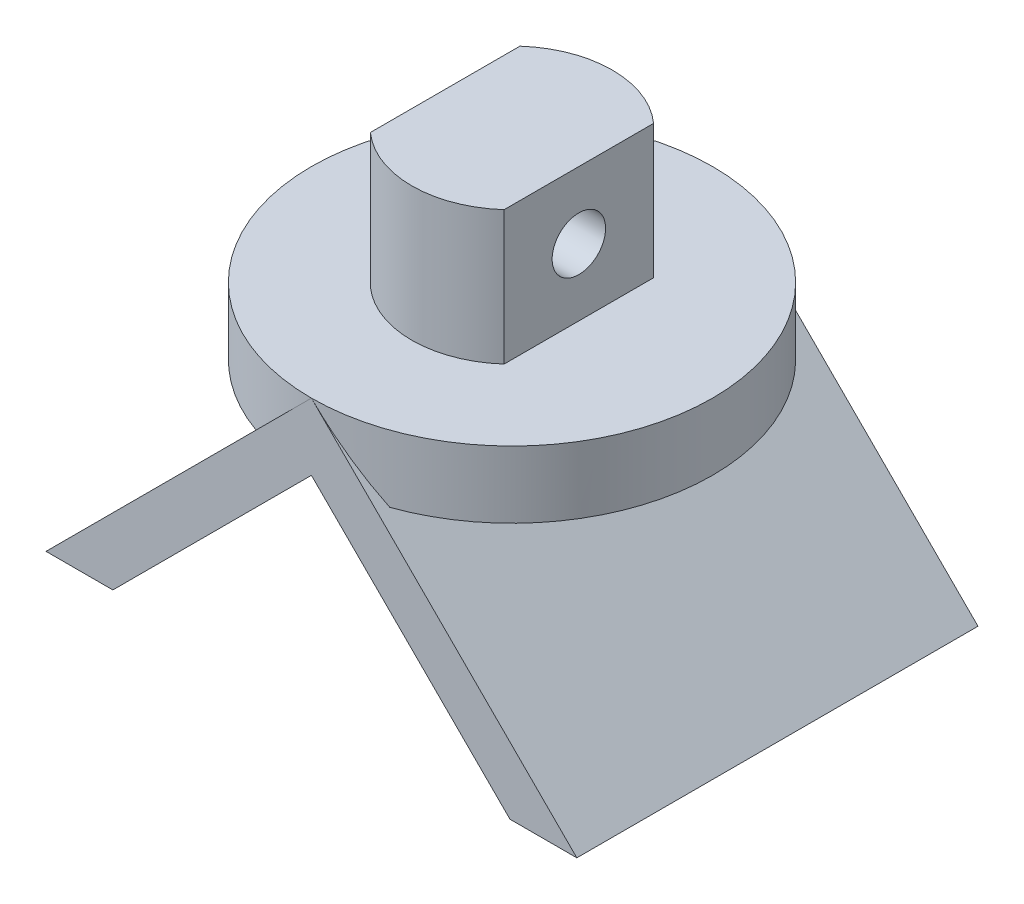
SolidWorks part; units mm, degrees
ref_plane "Plan de face" through (0, 0, 0) normal (0, 0, 1) x (1, 0, 0)
ref_plane "Plan de dessus" through (0, 0, 0) normal (0, 1, 0) x (1, 0, 0)
ref_plane "Plan de droite" through (0, 0, 0) normal (1, 0, 0) x (0, 0, -1)
sketch "Esquisse1" plane through (0, 0, 0) normal (0, 0, 1) x (1, 0, 0)
  line L0 (-14.8492, 0) -> (0, 14.8492)
  line L1 (0, 14.8492) -> (14.8492, 0)
  line L2 (14.8492, 0) -> (19.8492, 0)
  line L3 (19.8492, 0) -> (0, 19.8492)
  line L4 (0, 19.8492) -> (-19.8492, 0)
  line L5 (-19.8492, 0) -> (-14.8492, 0)
  line L6 (-14.8492, 0) -> (14.8492, 0) construction
  point P5 (0, 0)
  dimension "D1" = 5
  dimension "D2" = 21
extrude "Boss.-Extru.1" add sketch "Esquisse1" along normal blind 30
ref_plane "Plan1" through (0, 14.8492, 0) normal (0, 1, 0) x (1, 0, 0)
sketch "Esquisse2" plane through (0, 14.8492, 0) normal (0, 1, 0) x (1, 0, 0)
  line L0 (0, -30) -> (0, 0) construction
  circle A0 centre (0, -15) radius 15
  point P5 (0, -15)
extrude "Boss.-Extru.2" add sketch "Esquisse2" along normal up to vertex (5 mm away)
sketch "Esquisse5" plane through (0, 19.8492, 0) normal (0, 1, 0) x (1, 0, 0)
  line L0 (-5, -9.4098) -> (-5, -20.5902)
  line L1 (5, -9.4098) -> (5, -20.5902)
  line L2 (-5, -15) -> (5, -15) construction
  circle A0 centre (0, -15) radius 7.5
  arc A1 (0, -30) -> (0, 0) centre (0, -15) ccw construction
  point P13 (0, -15)
  dimension "D1" = 15
  dimension "D2" = 10
extrude "Boss.-Extru.3" add sketch "Esquisse5" along normal blind 10 contours L0 L2 L1 A0 | L2 L0 A0 L1
sketch "Esquisse7" plane through (-5, 0, 0) normal (-1, 0, 0) x (0, 0, 1)
  line L0 (9.4098, 19.8492) -> (20.5902, 29.8492) construction
  circle A0 centre (15, 24.8492) radius 2
  dimension "D1" = 4
extrude "Enlèv. mat.-Extru.1" cut sketch "Esquisse7" against normal blind 10
